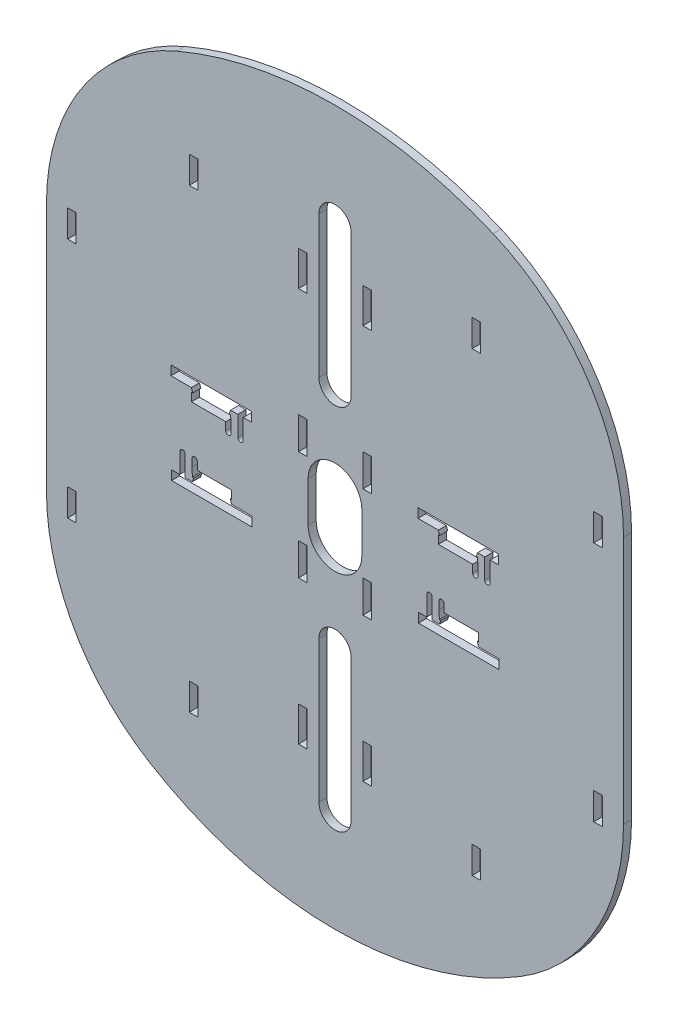
SolidWorks part; units mm, degrees
ref_plane "Front Plane" through (0, 0, 0) normal (0, 0, 1) x (1, 0, 0)
ref_plane "Top Plane" through (0, 0, 0) normal (0, 1, 0) x (1, 0, 0)
ref_plane "Right Plane" through (0, 0, 0) normal (1, 0, 0) x (0, 0, -1)
sketch "Sketch1" plane through (0, 0, 0) normal (0, 0, 1) x (1, 0, 0)
  line L0 (107.5, -45.3073) -> (107.5, 47.372) construction
  line L1 (107.5, -45.3073) -> (107.5, 47.372)
  line L2 (-107.5, -45.3073) -> (-107.5, 47.372) construction
  line L3 (-107.5, -45.3073) -> (-107.5, 47.372)
  circle A1 centre (0, 0) radius 133 construction
  arc A3 (-58.9286, 120.9399) -> (-107.5, 47.372) centre (-27.5, 47.372) ccw construction
  arc A4 (58.9286, 120.9399) -> (-58.9286, 120.9399) centre (0, -17) ccw construction
  arc A5 (107.5, 47.372) -> (58.9286, 120.9399) centre (27.5, 47.372) ccw construction
  arc A6 (69.0094, -113.6956) -> (107.5, -45.3073) centre (27.5, -45.3073) ccw construction
  arc A7 (-107.5, -45.3073) -> (-69.0094, -113.6956) centre (-27.5, -45.3073) ccw construction
  arc A8 (-58.9286, 120.9399) -> (-107.5, 47.372) centre (-27.5, 47.372) ccw
  arc A9 (58.9286, 120.9399) -> (-58.9286, 120.9399) centre (0, -17) ccw
  arc A10 (107.5, 47.372) -> (58.9286, 120.9399) centre (27.5, 47.372) ccw
  arc A11 (69.0094, -113.6956) -> (107.5, -45.3073) centre (27.5, -45.3073) ccw
  arc A12 (-69.0094, -113.6956) -> (69.0094, -113.6956) centre (0, 0) ccw
  arc A13 (-107.5, -45.3073) -> (-69.0094, -113.6956) centre (-27.5, -45.3073) ccw
extrude "Boss-Extrude1" add sketch "Sketch1" along normal up to vertex (3 mm away)
sketch "Sketch4" plane through (0, 0, 3) normal (0, 0, 1) x (1, 0, 0)
  line B0 (60.9, 18.6) -> (30.9, 18.6)
  line B1 (30.9, 18.6) -> (30.9, 15.1)
  line B2 (30.9, 15.1) -> (38.5, 15.1)
  line B3 (38.5, 15.1) -> (39, 13.6)
  line B4 (39, 13.6) -> (38.5, 13.6)
  line B5 (38.5, 13.6) -> (38.5, 10.5)
  line B6 (38.5, 10.5) -> (51.3, 10.5)
  line B7 (51.3, 10.5) -> (51.3, 7.6)
  line B8 (53.3, 7.6) -> (53.3, 10.5)
  line B9 (53.3, 10.5) -> (53.1, 13.6)
  line B10 (53.1, 13.6) -> (52.6, 13.6)
  line B11 (52.6, 13.6) -> (53.1, 15.1)
  line B12 (53.1, 15.1) -> (55.8, 15.1)
  line B13 (55.8, 15.1) -> (55.8, 7.6)
  line B14 (57.8, 7.6) -> (57.8, 15.1)
  line B15 (57.8, 15.1) -> (60.9, 15.1)
  line B16 (60.9, 15.1) -> (60.9, 18.6)
  arc B17 (51.3, 7.6) -> (53.3, 7.6) centre (52.3, 7.6) ccw
  arc B18 (55.8, 7.6) -> (57.8, 7.6) centre (56.8, 7.6) ccw
  line B19 (31.1, -18.6) -> (61.1, -18.6)
  line B20 (61.1, -18.6) -> (61.1, -15.1)
  line B21 (61.1, -15.1) -> (53.5, -15.1)
  line B22 (53.5, -15.1) -> (53, -13.6)
  line B23 (53, -13.6) -> (53.5, -13.6)
  line B24 (53.5, -13.6) -> (53.5, -10.5)
  line B25 (53.5, -10.5) -> (40.7, -10.5)
  line B26 (40.7, -10.5) -> (40.7, -7.6)
  line B27 (38.7, -7.6) -> (38.7, -10.5)
  line B28 (38.7, -10.5) -> (38.9, -13.6)
  line B29 (38.9, -13.6) -> (39.4, -13.6)
  line B30 (39.4, -13.6) -> (38.9, -15.1)
  line B31 (38.9, -15.1) -> (36.2, -15.1)
  line B32 (36.2, -15.1) -> (36.2, -7.6)
  line B33 (34.2, -7.6) -> (34.2, -15.1)
  line B34 (34.2, -15.1) -> (31.1, -15.1)
  line B35 (31.1, -15.1) -> (31.1, -18.6)
  arc B36 (40.7, -7.6) -> (38.7, -7.6) centre (39.7, -7.6) ccw
  arc B37 (36.2, -7.6) -> (34.2, -7.6) centre (35.2, -7.6) ccw
  line B38 (-60.9, -18.6) -> (-30.9, -18.6)
  line B39 (-30.9, -18.6) -> (-30.9, -15.1)
  line B40 (-30.9, -15.1) -> (-38.5, -15.1)
  line B41 (-38.5, -15.1) -> (-39, -13.6)
  line B42 (-39, -13.6) -> (-38.5, -13.6)
  line B43 (-38.5, -13.6) -> (-38.5, -10.5)
  line B44 (-38.5, -10.5) -> (-51.3, -10.5)
  line B45 (-51.3, -10.5) -> (-51.3, -7.6)
  line B46 (-53.3, -7.6) -> (-53.3, -10.5)
  line B47 (-53.3, -10.5) -> (-53.1, -13.6)
  line B48 (-53.1, -13.6) -> (-52.6, -13.6)
  line B49 (-52.6, -13.6) -> (-53.1, -15.1)
  line B50 (-53.1, -15.1) -> (-55.8, -15.1)
  line B51 (-55.8, -15.1) -> (-55.8, -7.6)
  line B52 (-57.8, -7.6) -> (-57.8, -15.1)
  line B53 (-57.8, -15.1) -> (-60.9, -15.1)
  line B54 (-60.9, -15.1) -> (-60.9, -18.6)
  arc B55 (-51.3, -7.6) -> (-53.3, -7.6) centre (-52.3, -7.6) ccw
  arc B56 (-55.8, -7.6) -> (-57.8, -7.6) centre (-56.8, -7.6) ccw
  line B57 (-31.1, 18.6) -> (-61.1, 18.6)
  line B58 (-61.1, 18.6) -> (-61.1, 15.1)
  line B59 (-61.1, 15.1) -> (-53.5, 15.1)
  line B60 (-53.5, 15.1) -> (-53, 13.6)
  line B61 (-53, 13.6) -> (-53.5, 13.6)
  line B62 (-53.5, 13.6) -> (-53.5, 10.5)
  line B63 (-53.5, 10.5) -> (-40.7, 10.5)
  line B64 (-40.7, 10.5) -> (-40.7, 7.6)
  line B65 (-38.7, 7.6) -> (-38.7, 10.5)
  line B66 (-38.7, 10.5) -> (-38.9, 13.6)
  line B67 (-38.9, 13.6) -> (-39.4, 13.6)
  line B68 (-39.4, 13.6) -> (-38.9, 15.1)
  line B69 (-38.9, 15.1) -> (-36.2, 15.1)
  line B70 (-36.2, 15.1) -> (-36.2, 7.6)
  line B71 (-34.2, 7.6) -> (-34.2, 15.1)
  line B72 (-34.2, 15.1) -> (-31.1, 15.1)
  line B73 (-31.1, 15.1) -> (-31.1, 18.6)
  arc B74 (-40.7, 7.6) -> (-38.7, 7.6) centre (-39.7, 7.6) ccw
  arc B75 (-36.2, 7.6) -> (-34.2, 7.6) centre (-35.2, 7.6) ccw
sketch_block_instance "T-slot-1"
sketch_block "T-slot" parameters "D2"=1, "D18"=1, "D1"=5, "D3"=0.5, "D4"=14.8, "D5"=0.2, "D6"=3.1, "D7"=1.5, "D8"=30, "D9"=3.5, "D10"=5, "D11"=6, "D12"=2.5, "D13"=5, "D14"=6, "D15"=7.3, "D16"=0.2, "D17"=1.5, "D19"=15, "D20"=2, "D21"=2.9
sketch_block_instance "T-slot-4"
sketch_block_instance "T-slot-5"
sketch_block_instance "T-slot-6"
extrude "spine T-slots" cut sketch "Sketch4" against normal up to next
sketch "Sketch2" plane through (0, 0, 3) normal (0, 0, 1) x (1, 0, 0)
  line L0 (13.6, 17.5) -> (13.6, 26.4777) construction
  line L1 (13.6, 26.36) -> (10.4, 26.36)
  line L2 (13.6, 26.36) -> (13.6, 14.36)
  line L3 (13.6, 14.36) -> (10.4, 14.36)
  line L4 (10.4, 26.36) -> (10.4, 14.36)
  line L6 (-60, 13.5) -> (-60, 10.5) construction
  line L7 (10.4, 17.5) -> (10.4, 26.4777) construction
  line L8 (13.6, 80) -> (10.4, 80)
  line L9 (13.6, 80) -> (13.6, 67)
  line L10 (13.6, 67) -> (10.4, 67)
  line L11 (10.4, 80) -> (10.4, 67)
  line L12 (0, 0) -> (-79.2133, 0) construction
  line L13 (0, 0) -> (0, -51.3748) construction
  line L14 (-13.6, 80) -> (-10.4, 80)
  line L15 (-10.4, 80) -> (-10.4, 67)
  line L16 (-13.6, 67) -> (-10.4, 67)
  line L17 (-13.6, 80) -> (-13.6, 67)
  line L18 (-13.6, 26.36) -> (-10.4, 26.36)
  line L19 (-10.4, 26.36) -> (-10.4, 14.36)
  line L20 (-13.6, 14.36) -> (-10.4, 14.36)
  line L21 (-13.6, 26.36) -> (-13.6, 14.36)
  line L22 (13.5, -14.36) -> (13.5, -26.36) construction
  line L23 (10.5, -14.36) -> (10.5, -26.36) construction
  line L24 (-10.5, -14.36) -> (-10.5, -26.36) construction
  line L25 (-13.5, -14.36) -> (-13.5, -26.36) construction
  line L26 (-13.5, -14.36) -> (-10.5, -14.36) construction
  line L27 (-13.5, -26.36) -> (-10.5, -26.36) construction
  line L28 (10.5, -80) -> (10.5, -67) construction
  line L29 (13.5, -67) -> (10.5, -67) construction
  line L30 (13.5, -67) -> (13.5, -80) construction
  line L31 (13.5, -80) -> (10.5, -80) construction
  line L32 (-13.5, -67) -> (-13.5, -80) construction
  line L33 (-10.5, -80) -> (-10.5, -67) construction
  line L34 (-13.5, -80) -> (-10.5, -80) construction
  line L35 (-13.5, -67) -> (-10.5, -67) construction
  line L36 (10.5, -14.36) -> (13.5, -14.36) construction
  line L37 (10.5, -26.36) -> (13.5, -26.36) construction
  line L38 (10.5, 26.36) -> (13.5, 26.36) construction
  line L39 (10.5, 14.36) -> (13.5, 14.36) construction
  line L40 (-13.5, 26.36) -> (-10.5, 26.36) construction
  line L41 (-13.5, 14.36) -> (-10.5, 14.36) construction
  line L46 (10.5, 26.36) -> (13.5, 26.36) construction
  line L47 (10.5, 14.36) -> (13.5, 14.36) construction
  line L48 (-13.5, 67) -> (-10.5, 67) construction
  line L49 (-13.5, 80) -> (-10.5, 80) construction
  line L50 (-13.5, 67) -> (-10.5, 67) construction
  line L51 (-13.5, 80) -> (-10.5, 80) construction
  line L52 (-10.5, 80) -> (-10.5, 67) construction
  line L53 (-13.5, 67) -> (-13.5, 80) construction
  line L54 (13.5, 80) -> (10.5, 80) construction
  line L55 (13.5, 67) -> (13.5, 80) construction
  line L56 (13.5, 67) -> (10.5, 67) construction
  line L57 (10.5, 80) -> (10.5, 67) construction
  line L58 (-13.6, -26.36) -> (-13.6, -14.36)
  line L59 (-13.6, -14.36) -> (-10.4, -14.36)
  line L60 (-10.4, -26.36) -> (-10.4, -14.36)
  line L61 (-13.6, -26.36) -> (-10.4, -26.36)
  line L62 (-13.6, -80) -> (-13.6, -67)
  line L63 (-13.6, -67) -> (-10.4, -67)
  line L64 (-10.4, -80) -> (-10.4, -67)
  line L65 (-13.6, -80) -> (-10.4, -80)
  line L66 (10.4, -80) -> (10.4, -67)
  line L67 (13.6, -67) -> (10.4, -67)
  line L68 (13.6, -80) -> (13.6, -67)
  line L69 (13.6, -80) -> (10.4, -80)
  line L70 (10.4, -26.36) -> (10.4, -14.36)
  line L71 (13.6, -14.36) -> (10.4, -14.36)
  line L72 (13.6, -26.36) -> (13.6, -14.36)
  line L73 (13.6, -26.36) -> (10.4, -26.36)
  line L74 (-13.5, 26.36) -> (-10.5, 26.36) construction
  line L99 (-13.5, 14.36) -> (-10.5, 14.36) construction
  line L113 (-13.5, 14.36) -> (-13.5, 26.36) construction
  line L114 (-10.5, 14.36) -> (-10.5, 26.36) construction
  line L115 (10.5, 14.36) -> (10.5, 26.36) construction
  line L116 (13.5, 14.36) -> (13.5, 26.36) construction
extrude "spine mounting slots" cut sketch "Sketch2" against normal up to next
sketch "Sketch5" plane through (0, 0, 3) normal (0, 0, 1) x (1, 0, 0)
  line L2 (0, 0) -> (90.2489, 0) construction
  line L4 (-54.19, -85) -> (54.29, -85) construction
  line L7 (0, 0) -> (0, 39.0523) construction
  line B0 (51.09, 79.95) -> (51.09, 90.05)
  line B1 (51.09, 79.95) -> (54.29, 79.95)
  line B2 (54.29, 79.95) -> (54.29, 90.05)
  line B3 (51.09, 90.05) -> (54.29, 90.05)
  line B4 (51.09, -90.05) -> (51.09, -79.95)
  line B5 (51.09, -90.05) -> (54.29, -90.05)
  line B6 (54.29, -90.05) -> (54.29, -79.95)
  line B7 (51.09, -79.95) -> (54.29, -79.95)
  line B8 (-54.29, 79.95) -> (-54.29, 90.05)
  line B9 (-54.29, 79.95) -> (-51.09, 79.95)
  line B10 (-51.09, 79.95) -> (-51.09, 90.05)
  line B11 (-54.29, 90.05) -> (-51.09, 90.05)
  line B12 (-54.29, -90.05) -> (-54.29, -79.95)
  line B13 (-54.29, -90.05) -> (-51.09, -90.05)
  line B14 (-51.09, -90.05) -> (-51.09, -79.95)
  line B15 (-54.29, -79.95) -> (-51.09, -79.95)
  line B16 (96.4, 39.95) -> (96.4, 50.05)
  line B17 (96.4, 39.95) -> (99.6, 39.95)
  line B18 (99.6, 39.95) -> (99.6, 50.05)
  line B19 (96.4, 50.05) -> (99.6, 50.05)
  line B20 (96.4, -50.05) -> (96.4, -39.95)
  line B21 (96.4, -50.05) -> (99.6, -50.05)
  line B22 (99.6, -50.05) -> (99.6, -39.95)
  line B23 (96.4, -39.95) -> (99.6, -39.95)
  line B24 (-99.6, -50.05) -> (-99.6, -39.95)
  line B25 (-99.6, -50.05) -> (-96.4, -50.05)
  line B26 (-96.4, -50.05) -> (-96.4, -39.95)
  line B27 (-99.6, -39.95) -> (-96.4, -39.95)
  line B28 (-99.6, 39.95) -> (-99.6, 50.05)
  line B29 (-99.6, 39.95) -> (-96.4, 39.95)
  line B30 (-96.4, 39.95) -> (-96.4, 50.05)
  line B31 (-99.6, 50.05) -> (-96.4, 50.05)
sketch_block_instance "external-tooth-slot-1"
sketch_block "external-tooth-slot" parameters "D1"=10.1, "D2"=3.2, "D3"=9.7492, "D4"=9.7492, "D5"=3.2
sketch_block_instance "external-tooth-slot-3"
sketch_block_instance "external-tooth-slot-4"
sketch_block_instance "external-tooth-slot-5"
sketch_block_instance "external-tooth-slot-6"
sketch_block_instance "external-tooth-slot-7"
sketch_block_instance "external-tooth-slot-9"
sketch_block_instance "external-tooth-slot-10"
extrude "side plate slots" cut sketch "Sketch5" against normal up to next
sketch "Sketch3" plane through (0, 0, 3) normal (0, 0, 1) x (1, 0, 0)
  line L0 (0, -94.9135) -> (0, -42.11) construction
  line L1 (0, -133) -> (0, 133) construction
  line L2 (0, -80) -> (0, 80) construction
  line L3 (-6, -94.9135) -> (-6, -42.11)
  line L4 (6, -94.9135) -> (6, -42.11)
  line L5 (0, 0) -> (-39.2879, 0) construction
  line L6 (0, 94.9135) -> (0, 42.11) construction
  line L7 (-6, 94.9135) -> (-6, 42.11)
  line L8 (6, 94.9135) -> (6, 42.11)
  line L9 (0, 7.5) -> (0, -7.5) construction
  line L10 (10, 7.5) -> (10, -7.5)
  line L11 (-10, 7.5) -> (-10, -7.5)
  arc A0 (-6, -94.9135) -> (6, -94.9135) centre (0, -94.9135) ccw
  arc A1 (6, -42.11) -> (-6, -42.11) centre (0, -42.11) ccw
  arc A2 (-6, 94.9135) -> (6, 94.9135) centre (0, 94.9135) cw
  arc A3 (6, 42.11) -> (-6, 42.11) centre (0, 42.11) cw
  arc A4 (10, 7.5) -> (-10, 7.5) centre (0, 7.5) ccw
  arc A5 (-10, -7.5) -> (10, -7.5) centre (0, -7.5) ccw
  point P6 (0, -68.5117)
  point P16 (0, 68.5117)
  point P23 (0, 0)
  dimension "D3" = 15
  dimension "D1" = 12
  dimension "D2" = 20
extrude "linkage clearance" cut sketch "Sketch3" against normal up to next
